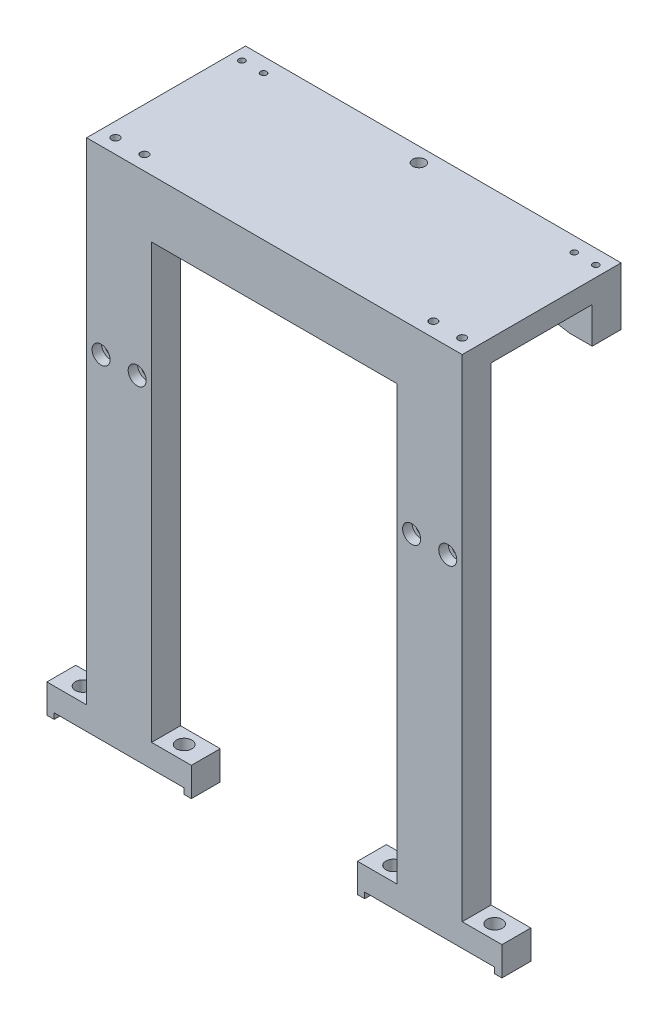
SolidWorks part; units mm, degrees
material "6061 Alloy"
ref_plane "Front Plane" through (0, 0, 0) normal (0, 0, 1) x (1, 0, 0)
ref_plane "Top Plane" through (0, 0, 0) normal (0, 1, 0) x (1, 0, 0)
ref_plane "Right Plane" through (0, 0, 0) normal (1, 0, 0) x (0, 0, -1)
sketch "Sketch1" plane through (0, 0, 0) normal (0, 0, 1) x (1, 0, 0)
  line L1 (-82.55, -114.3) -> (82.55, -114.3)
  line L2 (-82.55, -114.3) -> (-82.55, 114.3)
  line L3 (-82.55, 114.3) -> (82.55, 114.3)
  line L4 (82.55, -114.3) -> (82.55, 114.3)
  line L5 (-82.55, -114.3) -> (82.55, 114.3) construction
  line L6 (-82.55, 114.3) -> (82.55, -114.3) construction
  point P0 (0, 0)
  dimension "D1" = 228.6
  dimension "D2" = 165.1
extrude "Boss-Extrude1" add sketch "Sketch1" along normal blind 12.7
sketch "Sketch2" plane through (0, 0, 12.7) normal (0, 0, 1) x (1, 0, 0)
  line L0 (-82.55, -114.3) -> (82.55, -114.3) construction
  line L1 (-53.975, -114.3) -> (53.975, -114.3)
  line L2 (-53.975, -114.3) -> (-53.975, 88.9)
  line L3 (-53.975, 88.9) -> (53.975, 88.9)
  line L4 (53.975, -114.3) -> (53.975, 88.9)
  line L5 (-82.55, 114.3) -> (-82.55, -114.3) construction
  dimension "D1" = 203.2
  dimension "D2" = 107.95
  dimension "D3" = 28.575
extrude "Cut-Extrude1" cut sketch "Sketch2" against normal through all
sketch "Sketch3" plane through (0, 0, 0) normal (0, 0, -1) x (-1, 0, 0)
  line L0 (82.55, 114.3) -> (82.55, -114.3) construction
  line L1 (-82.55, 114.3) -> (82.55, 114.3)
  line L2 (-82.55, 114.3) -> (-82.55, 104.775)
  line L3 (-82.55, 104.775) -> (82.55, 104.775)
  line L4 (82.55, 114.3) -> (82.55, 104.775)
  dimension "D1" = 9.525
extrude "Boss-Extrude2" add sketch "Sketch3" along normal blind 57.15
sketch "Sketch4" plane through (0, 0, -57.15) normal (0, 0, -1) x (-1, 0, 0)
  line L7 (-82.55, 104.775) -> (-63.5, 104.775)
  line L8 (-82.55, 104.775) -> (-82.55, 88.9)
  line L9 (-82.55, 88.9) -> (-63.5, 88.9)
  line L10 (-63.5, 104.775) -> (-63.5, 88.9)
  dimension "D1" = 15.875
  dimension "D2" = 19.05
extrude "Boss-Extrude3" add sketch "Sketch4" against normal blind 12.7
mirror "Mirror1" about plane through (0, 0, 0) normal (1, 0, 0) of "Boss-Extrude3"
sketch "Sketch5" plane through (0, 0, -57.15) normal (0, 0, -1) x (-1, 0, 0)
  line L5 (-72.5032, 88.9) -> (-63.5, 90.4875)
  line L6 (-82.55, 88.9) -> (-63.5, 88.9) construction
  line L7 (-63.5, 88.9) -> (-63.5, 104.775) construction
  line L8 (-63.5, 90.4875) -> (-63.5, 88.9)
  line L9 (-63.5, 88.9) -> (-72.5032, 88.9)
  dimension "D1" = 1.5875
  dimension "D2" = 80
extrude "Cut-Extrude2" cut sketch "Sketch5" against normal up to next
mirror "Mirror2" about plane through (0, 0, 0) normal (1, 0, 0) of "Cut-Extrude2"
sketch "Sketch7" plane through (0, 0, 12.7) normal (0, 0, 1) x (1, 0, 0)
  line L0 (-82.55, -114.3) -> (-53.975, -114.3) construction
  line L1 (-100.0125, -101.6) -> (-36.5125, -101.6)
  line L2 (-100.0125, -101.6) -> (-100.0125, -114.3)
  line L3 (-100.0125, -114.3) -> (-36.5125, -114.3)
  line L4 (-36.5125, -101.6) -> (-36.5125, -114.3)
  line L5 (-100.0125, -101.6) -> (-36.5125, -114.3) construction
  line L6 (-100.0125, -114.3) -> (-36.5125, -101.6) construction
  line L7 (-82.55, 114.3) -> (-82.55, -114.3) construction
  point P0 (-68.2625, -107.95)
  dimension "D1" = 0
  dimension "D2" = 63.5
  dimension "D3" = 17.4625
  dimension "D4" = 12.7
extrude "Boss-Extrude4" add sketch "Sketch7" against normal blind 12.7
sketch "Sketch8" plane through (0, -114.3, 0) normal (0, -1, 0) x (-1, 0, 0)
  line L0 (100.0125, -12.7) -> (36.5125, -12.7) construction
  line L1 (96.8375, 0) -> (39.6875, 0)
  line L2 (96.8375, 0) -> (96.8375, -12.7)
  line L3 (96.8375, -12.7) -> (39.6875, -12.7)
  line L4 (39.6875, 0) -> (39.6875, -12.7)
  line L5 (96.8375, 0) -> (39.6875, -12.7) construction
  line L6 (96.8375, -12.7) -> (39.6875, 0) construction
  line L8 (100.0125, 0) -> (100.0125, -12.7) construction
  line L9 (36.5125, 0) -> (36.5125, -12.7) construction
  point P0 (68.2625, -6.35)
  dimension "D1" = 12.7
  dimension "D2" = 3.175
  dimension "D3" = 3.175
extrude "Cut-Extrude4" cut sketch "Sketch8" against normal blind 2.54
mirror "Mirror3" about plane through (0, 0, 0) normal (1, 0, 0) of "Cut-Extrude4", "Boss-Extrude4"
hole_wizard "#8-32 Tapped Hole1" positions "Sketch11" profile "Sketch10" tap size "#8-32" standard "ANSI Inch"
sketch "Sketch11" plane through (0, 114.3, 0) normal (0, 1, 0) x (1, 0, 0)
  line L0 (-82.55, 0) -> (-82.55, -12.7) construction
  line L1 (-82.55, -12.7) -> (-82.55, 57.15) construction
  line L2 (82.55, 0) -> (82.55, -12.7) construction
  line L3 (82.55, -12.7) -> (82.55, 57.15) construction
  line L4 (82.55, -12.7) -> (-82.55, -12.7) construction
  point P0 (-76.2, -6.35)
  point P2 (-63.5, -6.35)
  point P4 (63.5, -6.35)
  point P6 (76.2, -6.35)
  dimension "D1" = 6.35
  dimension "D2" = 19.05
  dimension "D3" = 6.35
  dimension "D4" = 19.05
  dimension "D5" = 6.35
  dimension "D6" = 6.35
  dimension "D7" = 6.35
  dimension "D8" = 6.35
cosmetic thread "Hole Thread1" parameters "D1"=3.048, "D2"=4.1656
cosmetic thread "Hole Thread2" parameters "D1"=3.048, "D2"=4.1656
cosmetic thread "Hole Thread3" parameters "D1"=3.048, "D2"=4.1656
cosmetic thread "Hole Thread4" parameters "D1"=3.048, "D2"=4.1656
sketch "Sketch10" plane through (-76.2, 114.3, 6.35) normal (1, 0, 0) x (0, 0, 1)
  line L0 (0, 0) -> (0, 13.7378)
  line L1 (0, 13.7378) -> (1.7272, 12.7)
  line L2 (1.7272, 12.7) -> (1.7272, 0)
  line L5 (1.7272, 0) -> (0, 0)
  line L10 (0, 13.7378) -> (-1.7272, 12.7) construction
  line L11 (0, -6.35) -> (0, 107.95) construction
  dimension "Tap Drill Dia." = 3.4544
  dimension "Tap Drill Depth" = 12.7
  dimension "Drill Angle" = 118
hole_wizard "1/4 Clearance Hole1" positions "Sketch12" profile "Sketch13" hole size "1/4" standard "ANSI Inch"
sketch "Sketch12" plane through (0, -101.6, 0) normal (0, 1, 0) x (1, 0, 0)
  line L0 (-100.0125, 0) -> (-100.0125, -12.7) construction
  line L1 (-82.55, 0) -> (-100.0125, 0) construction
  line L2 (-36.5125, 0) -> (-53.975, 0) construction
  line L3 (-36.5125, 0) -> (-36.5125, -12.7) construction
  line L4 (36.5125, 0) -> (36.5125, -12.7) construction
  line L5 (36.5125, 0) -> (53.975, 0) construction
  line L6 (82.55, 0) -> (100.0125, 0) construction
  line L7 (100.0125, 0) -> (100.0125, -12.7) construction
  point P0 (-90.4875, -6.35)
  point P2 (-46.0375, -6.35)
  point P4 (46.0375, -6.35)
  point P6 (90.4875, -6.35)
  dimension "D1" = 9.525
  dimension "D2" = 6.35
  dimension "D3" = 6.35
  dimension "D4" = 9.525
  dimension "D5" = 9.525
  dimension "D6" = 6.35
  dimension "D7" = 6.35
  dimension "D8" = 9.525
sketch "Sketch13" plane through (-90.4875, -101.6, 6.35) normal (1, 0, 0) x (0, 0, 1)
  line L0 (0, 0) -> (0, 10.16)
  line L1 (0, 10.16) -> (3.3782, 10.16)
  line L2 (3.3782, 10.16) -> (3.3782, 0)
  line L5 (3.3782, 0) -> (0, 0)
  line L11 (0, -6.35) -> (0, 107.95) construction
  dimension "Thru Hole Dia." = 6.7564
  dimension "Thru Hole Depth" = 10.16
hole_wizard "#6-32 Tapped Hole2" positions "Sketch14" profile "Sketch15" tap size "#6-32" standard "ANSI Inch" end condition through all
sketch "Sketch14" plane through (0, 88.9, 0) normal (0, -1, 0) x (-1, 0, 0)
  line L0 (82.55, 57.15) -> (72.5032, 57.15) construction
  line L1 (63.5, 57.15) -> (72.5032, 57.15) construction
  line L2 (-63.5, 57.15) -> (-72.5032, 57.15) construction
  line L3 (-82.55, 57.15) -> (-72.5032, 57.15) construction
  line L4 (82.55, 44.45) -> (82.55, 57.15) construction
  point P0 (77.7875, 50.8)
  point P2 (68.2625, 50.8)
  point P5 (-77.7875, 50.8)
  point P7 (-68.2625, 50.8)
  dimension "D1" = 6.35
  dimension "D2" = 6.35
  dimension "D3" = 6.35
  dimension "D4" = 6.35
  dimension "D5" = 4.7625
  dimension "D6" = 9.525
  dimension "D7" = 4.7625
  dimension "D8" = 9.525
sketch "Sketch15" plane through (-77.7875, 88.9, -50.8) normal (1, 0, 0) x (0, 0, -1)
  line L0 (0, 0) -> (0, 25.4)
  line L1 (0, 25.4) -> (1.3525, 25.4)
  line L2 (1.3525, 25.4) -> (1.3525, 0)
  line L5 (1.3525, 0) -> (0, 0)
  line L11 (0, -6.35) -> (0, 107.95) construction
  dimension "Thru Tap Drill Dia." = 2.7051
  dimension "Thru Tap Drill Depth" = 25.4
cosmetic thread "Hole Thread5" parameters "D2"=3.5052
cosmetic thread "Hole Thread6" parameters "D2"=3.5052
cosmetic thread "Hole Thread7" parameters "D2"=3.5052
cosmetic thread "Hole Thread8" parameters "D2"=3.5052
hole_wizard "1/4-28 Tapped Hole1" positions "Sketch16" profile "Sketch17" tap size "1/4-28" standard "ANSI Inch" end condition through all
sketch "Sketch16" plane through (0, 114.3, 0) normal (0, 1, 0) x (1, 0, 0)
  line L0 (-82.55, 57.15) -> (82.55, 57.15) construction
  point P0 (0, 50.8)
  dimension "D1" = 6.35
sketch "Sketch17" plane through (0, 114.3, -50.8) normal (1, 0, 0) x (0, 0, 1)
  line L0 (0, 0) -> (0, 228.6)
  line L1 (0, 228.6) -> (2.7051, 228.6)
  line L2 (2.7051, 228.6) -> (2.7051, 0)
  line L5 (2.7051, 0) -> (0, 0)
  line L11 (0, -6.35) -> (0, 107.95) construction
  dimension "Thru Tap Drill Dia." = 5.4102
  dimension "Thru Tap Drill Depth" = 228.6
cosmetic thread "Hole Thread9" parameters "D2"=6.35
hole_wizard "CBORE for #8 Socket Head Cap Screw1" positions "Sketch18" profile "Sketch19" counterbore size "#8" standard "ANSI Inch" end condition up to next
sketch "Sketch18" plane through (0, 0, 12.7) normal (0, 0, 1) x (1, 0, 0)
  line L0 (-82.55, 114.3) -> (-82.55, -101.6) construction
  line L1 (-53.975, 88.9) -> (-53.975, -101.6) construction
  line L2 (53.975, -101.6) -> (53.975, 88.9) construction
  line L3 (82.55, -101.6) -> (82.55, 114.3) construction
  point P0 (-76.2, 34.925)
  point P2 (-60.325, 34.925)
  point P4 (60.325, 34.925)
  point P6 (76.2, 34.925)
  dimension "D1" = 6.35
  dimension "D2" = 6.35
  dimension "D3" = 6.35
  dimension "D4" = 6.35
  dimension "D5" = 136.525
  dimension "D6" = 136.525
  dimension "D7" = 136.525
  dimension "D8" = 136.525
sketch "Sketch19" plane through (-76.2, 34.925, 12.7) normal (1, 0, 0) x (0, -1, 0)
  line L0 (0, 0) -> (0, 12.7)
  line L1 (0, 12.7) -> (2.2479, 12.7)
  line L3 (2.2479, 12.7) -> (2.2479, 4.1656)
  line L4 (2.2479, 4.1656) -> (3.9687, 4.1656)
  line L5 (3.9687, 4.1656) -> (3.9687, 0)
  line L7 (3.9687, 0) -> (0, 0)
  line L11 (0, -6.35) -> (0, 107.95) construction
  dimension "Thru Hole Dia." = 4.4958
  dimension "Thru Hole Depth" = 12.7
  dimension "C'Bore Dia." = 7.9375
  dimension "C'Bore Depth" = 4.1656
